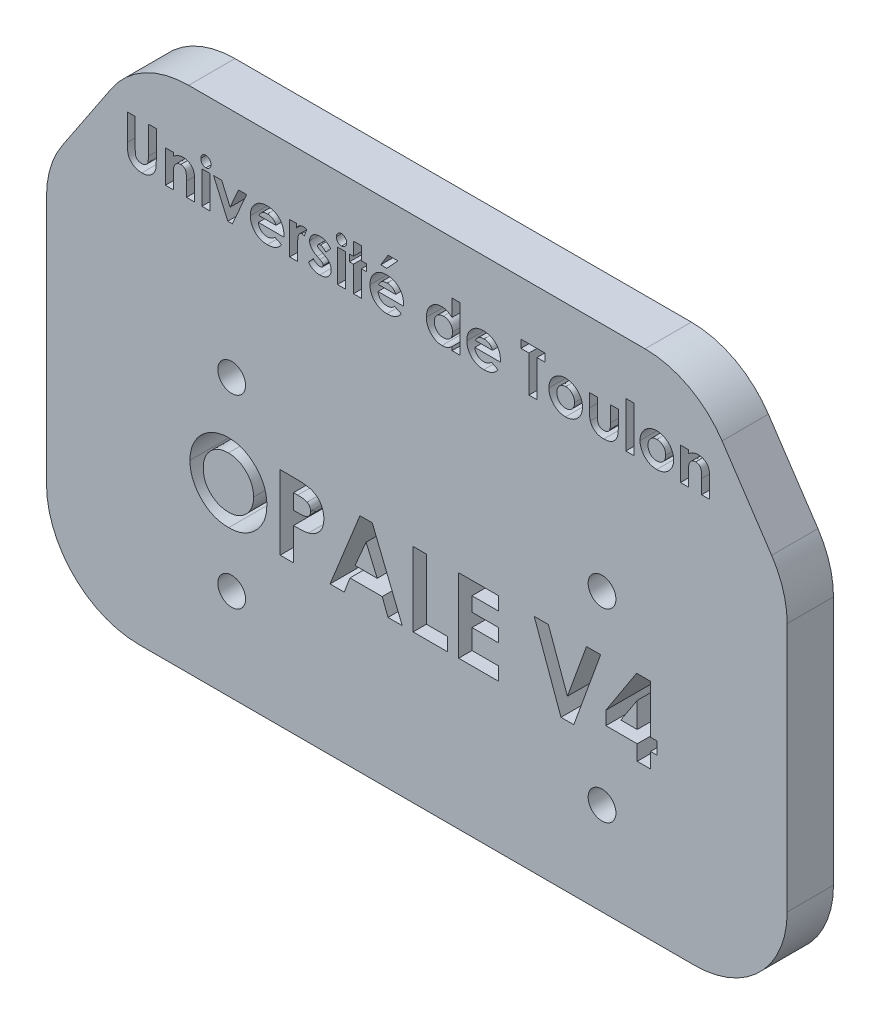
SolidWorks part; units mm, degrees
ref_plane "Plan de face" through (0, 0, 0) normal (0, 0, 1) x (1, 0, 0)
ref_plane "Plan de dessus" through (0, 0, 0) normal (0, 1, 0) x (1, 0, 0)
ref_plane "Plan de droite" through (0, 0, 0) normal (1, 0, 0) x (0, 0, -1)
sketch "Esquisse1" plane through (0, 0, 0) normal (0, 0, 1) x (1, 0, 0)
  line L0 (-40, 0) -> (40, 0)
  line L1 (2.5, 20) -> (40, 20) construction
  line L2 (-40, 20) -> (-40, 40)
  line L3 (0, 62.4131) -> (0, -5.9928) construction
  line L4 (-40, 20) -> (-40, 0)
  line L5 (40, 40) -> (30, 55)
  line L6 (30, 55) -> (-30, 55)
  line L7 (-30, 55) -> (-40, 40)
  line L9 (-40, 40) -> (40, 40) construction
  line L24 (40, 20) -> (40, 40)
  line L44 (40, 0) -> (40, 20)
  circle A0 centre (20, 30) radius 1.5
  circle A1 centre (-20, 30) radius 1.5
  circle A2 centre (-20, 10) radius 1.5
  circle A3 centre (20, 10) radius 1.5
  point P1 (0, 0)
  point P8 (0, 40)
  point P26 (0, 0)
  dimension "D10" = 3
  dimension "D3" = 15
  dimension "D1" = 40
  dimension "D2" = 80
  dimension "D4" = 10
  dimension "D11" = 40
  dimension "D12" = 20
extrude "Boss.-Extru.1" add sketch "Esquisse1" along normal blind 5
sketch "Esquisse2" plane through (0, 0, 5) normal (0, 0, 1) x (1, 0, 0)
  text T0 "Université de Toulon" font "Century Gothic" height 4.8
  text T1 "<b>OPALE V4</b>\r\n" font "Century Gothic" height 8
extrude "Enlèv. mat.-Extru.1" cut sketch "Esquisse2" against normal through all
fillet "Congé2" radius 10 6 edges at (-40, 40, 2.5) (-30, 55, 2.5) (40, 40, 2.5) (30, 55, 2.5) (-40, 0, 2.5) (40, 0, 2.5)
